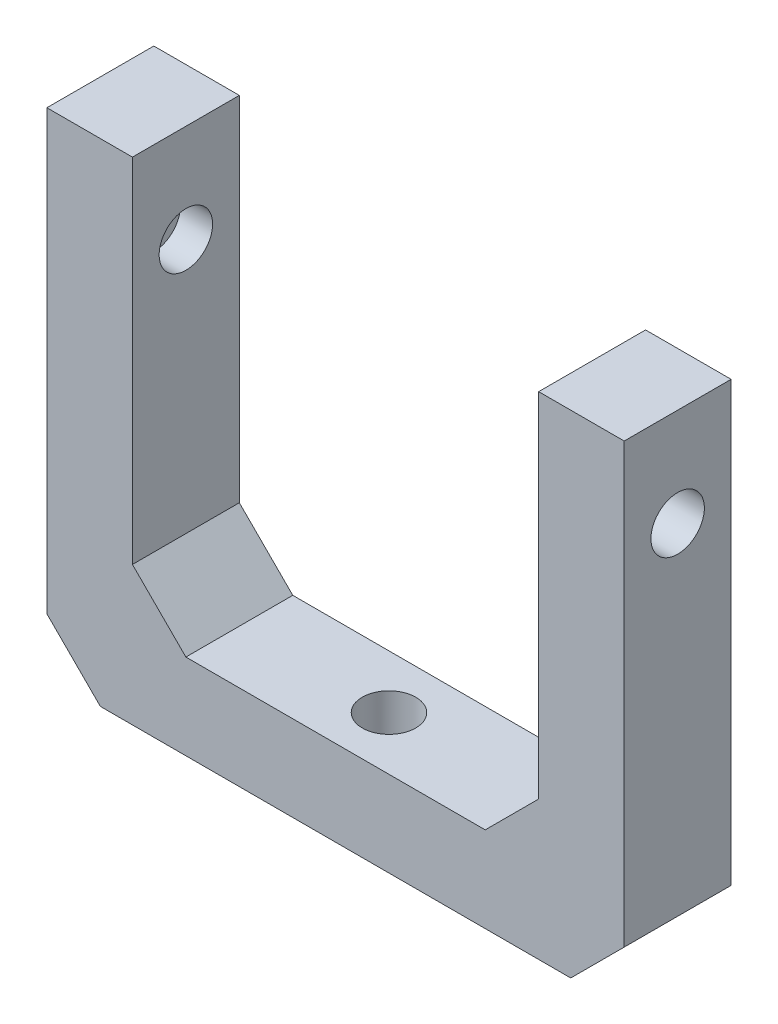
SolidWorks part; units mm, degrees
ref_plane "Front Plane" through (0, 0, 0) normal (0, 0, 1) x (1, 0, 0)
ref_plane "Top Plane" through (0, 0, 0) normal (0, 1, 0) x (1, 0, 0)
ref_plane "Right Plane" through (0, 0, 0) normal (1, 0, 0) x (0, 0, -1)
sketch "Sketch1" plane through (0, 0, 0) normal (0, 0, 1) x (1, 0, 0)
  line L0 (-27, 38) -> (-19, 38)
  line L1 (-19, 38) -> (-19, 5)
  line L2 (-14, 0) -> (14, 0)
  line L3 (19, 5) -> (19, 38)
  line L4 (19, 38) -> (27, 38)
  line L5 (27, 38) -> (27, -3)
  line L6 (22, -8) -> (-22, -8)
  line L7 (-27, -3) -> (-27, 38)
  line L8 (-19, 5) -> (-14, 0)
  line L9 (-22, -8) -> (-27, -3)
  line L10 (14, 0) -> (19, 5)
  line L11 (27, -3) -> (22, -8)
  point P3 (-19, 0)
  point P4 (19, 0)
  point P7 (27, -8)
  point P8 (-27, -8)
  dimension "D1" = 8
  dimension "D2" = 8
  dimension "D3" = 38
  dimension "D4" = 46
extrude "Boss-Extrude1" add sketch "Sketch1" along normal blind 10
sketch "Sketch2" plane through (-19, 0, 0) normal (1, 0, 0) x (0, 0, -1)
  line L0 (-10, 38) -> (0, 38) construction
  circle A0 centre (-5, 28.83) radius 2.5
  point P4 (-5, 38)
  dimension "D1" = 5
  dimension "D2" = 9.17
extrude "Cut-Extrude1" cut sketch "Sketch2" against normal blind 3 and the other way up to next
sketch "Sketch3" plane through (19, 0, 0) normal (-1, 0, 0) x (0, 0, 1)
  line L2 (5, 28.5036) -> (5, 16.5036) construction
  line L3 (8.5, 28.5036) -> (8.5, 16.5036)
  line L4 (1.5, 28.5036) -> (1.5, 16.5036)
  arc A2 (8.5, 28.5036) -> (1.5, 28.5036) centre (5, 28.5036) ccw
  arc A3 (1.5, 16.5036) -> (8.5, 16.5036) centre (5, 16.5036) ccw
  point P2 (5, 22.5036)
  point P8 (5, 32.0036)
  point P9 (5, 13.0036)
  dimension "D1" = 7
  dimension "D2" = 19
extrude "Cut-Extrude2" cut sketch "Sketch3" against normal blind 3
sketch "Sketch4" plane through (0, -8, 0) normal (0, -1, 0) x (1, 0, 0)
  line L0 (22, 10) -> (22, 0) construction
  circle A0 centre (0, 5) radius 2.5
  point P7 (22, 5)
  dimension "D1" = 5
extrude "Cut-Extrude3" cut sketch "Sketch4" against normal up to next
sketch "Sketch5" plane through (0, -8, 0) normal (0, -1, 0) x (1, 0, 0)
  line L1 (-19, 8.5) -> (19, 8.5)
  line L2 (-19, 8.5) -> (-19, 1.5)
  line L3 (-19, 1.5) -> (19, 1.5)
  line L4 (19, 8.5) -> (19, 1.5)
  line L5 (-19, 8.5) -> (19, 1.5) construction
  line L6 (-19, 1.5) -> (19, 8.5) construction
  point P0 (0, 5)
  dimension "D1" = 38
  dimension "D2" = 7
extrude "Cut-Extrude4" cut sketch "Sketch5" against normal blind 4
